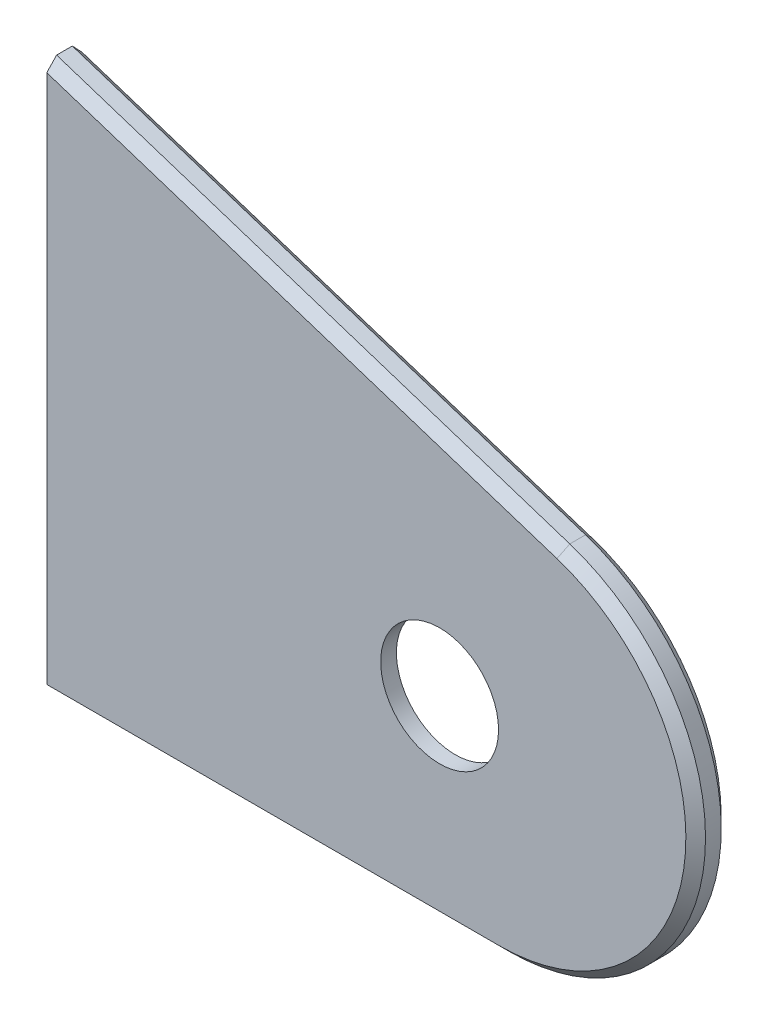
SolidWorks part; units mm, degrees
material "6061 合金"
ref_plane "前视基准面" through (0, 0, 0) normal (0, 0, 1) x (1, 0, 0)
ref_plane "上视基准面" through (0, 0, 0) normal (0, 1, 0) x (1, 0, 0)
ref_plane "右视基准面" through (0, 0, 0) normal (1, 0, 0) x (0, 0, -1)
other "Configuration Table"
sketch "草图1" plane through (0, 0, 0) normal (0, 0, 1) x (1, 0, 0)
  line L0 (0, 0) -> (0, 280)
  line L1 (0, 280) -> (861.7514, 0)
  line L3 (861.7514, 0) -> (0, 0)
  circle A0 centre (200, 100) radius 85 construction
  circle A1 centre (200, 100) radius 30
  dimension "D1" = 170
  dimension "D4" = 60
  dimension "D2" = 200
  dimension "D3" = 72
  dimension "D5" = 280
  dimension "D6" = 100
extrude "凸台-拉伸1" add sketch "草图1" along normal blind 8
fillet "圆角1" radius 100 1 edges at (861.7514, 0, 4)
sketch "草图2" plane through (0, 0, 0) normal (0, 0, 1) x (1, 0, 0)
  line L0 (10, 266.2362) -> (10, 35.359)
  line L1 (30, 10) -> (230.3762, 10)
  line L2 (10, 266.2362) -> (122.2414, 229.7667)
  line L3 (0, 0) -> (230.3762, 0)
  line L4 (261.2779, 195.1057) -> (0, 280)
  line L5 (0, 280) -> (0, 0)
  line L6 (0, 0) -> (230.3762, 0)
  line L7 (261.2779, 195.1057) -> (0, 280)
  line L8 (0, 280) -> (0, 0)
  line L9 (10, 35.359) -> (122.2414, 229.7667)
  line L10 (30, 10) -> (151.4105, 220.2891)
  line L11 (151.4105, 220.2891) -> (258.1878, 185.5951)
  line L12 (10, 35.359) -> (10, 10) construction
  line L13 (10, 10) -> (30, 10) construction
  arc A0 (230.3762, 10) -> (258.1878, 185.5951) centre (230.3762, 100) ccw
  arc A1 (230.3762, 0) -> (261.2779, 195.1057) centre (230.3762, 100) ccw
  arc A2 (230.3762, 0) -> (261.2779, 195.1057) centre (230.3762, 100) ccw
  dimension "D5" = 10
  dimension "D2" = 10
  dimension "D3" = 10
  dimension "D4" = 10
  dimension "D6" = 30
  dimension "D7" = 60
  dimension "D8" = 20
  dimension "D1" = 0
extrude "凸台-拉伸2" add sketch "草图2" against normal blind 10
fillet "圆角2" radius 10 5 edges at (10, 35.359, -5) (30, 10, -5) (122.2414, 229.7667, -5) (151.4105, 220.2891, -5) (10, 266.2362, -5)
chamfer "倒角1" distance 5 angle 45 6 edges at (115.1881, 0, -10) (130.639, 237.5528, -10) (329.1451, 84.3566, -10) (115.1881, 0, 8) (130.639, 237.5528, 8) (329.1451, 84.3566, 8)
